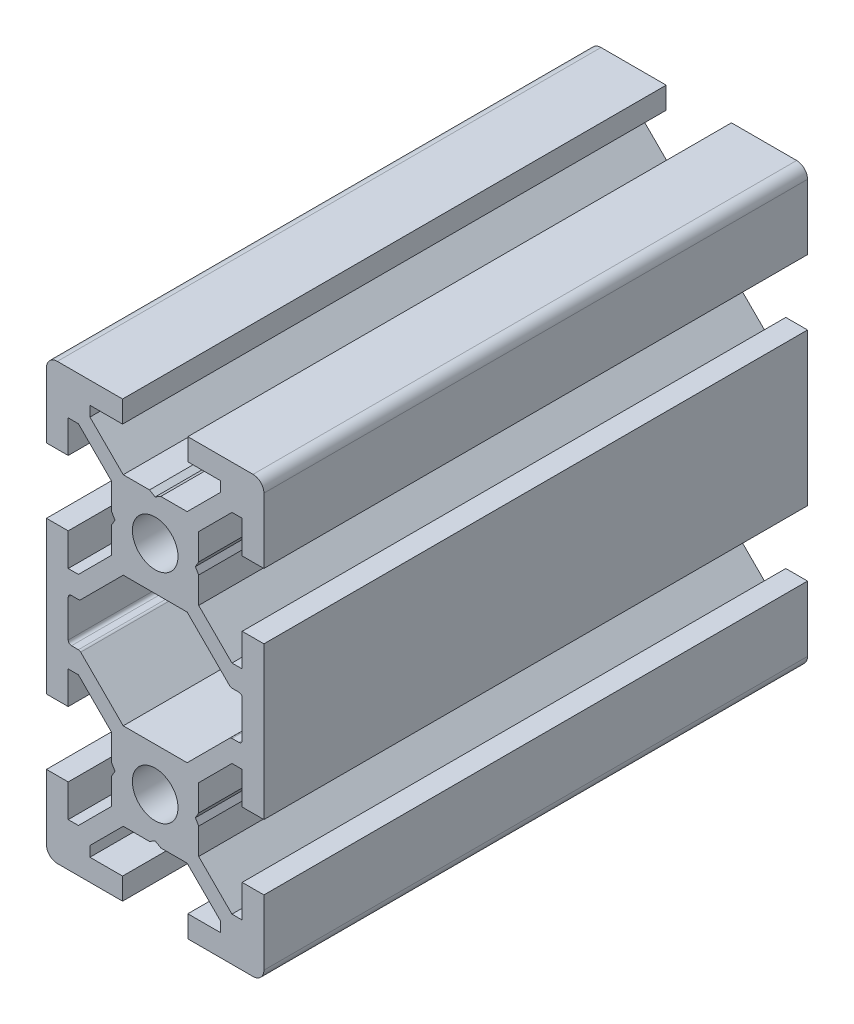
SolidWorks part; units mm, degrees
ref_plane "Front Plane" through (0, 0, 0) normal (0, 0, 1) x (1, 0, 0)
ref_plane "Top Plane" through (0, 0, 0) normal (0, 1, 0) x (1, 0, 0)
ref_plane "Right Plane" through (0, 0, 0) normal (1, 0, 0) x (0, 0, -1)
sketch "Sketch1" plane through (0, 0, 0) normal (0, 0, 1) x (1, 0, 0)
  line L0 (-8, -16) -> (-8, -13)
  line L1 (-8, -13) -> (-10, -13)
  line L2 (-10, -13) -> (-10, -19)
  line L3 (-9, -20) -> (-3, -20)
  line L4 (-3, -20) -> (-3, -18)
  line L5 (-3, -18) -> (-6, -18)
  line L6 (-6, -18) -> (-6, -17.0607)
  line L7 (-6, -17.0607) -> (-2.9393, -14)
  line L8 (-2.9393, -14) -> (-0.5196, -14)
  line L9 (-0.5196, -14) -> (0, -13.7)
  line L10 (0, -13.7) -> (0.5196, -14)
  line L11 (0.5196, -14) -> (2.9393, -14)
  line L12 (2.9393, -14) -> (6, -17.0607)
  line L13 (6, -17.0607) -> (6, -18)
  line L14 (6, -18) -> (3, -18)
  line L15 (3, -18) -> (3, -20)
  line L16 (3, -20) -> (9, -20)
  line L17 (10, -19) -> (10, -13)
  line L18 (10, -13) -> (8, -13)
  line L19 (8, -13) -> (8, -16)
  line L20 (8, -16) -> (7.0607, -16)
  line L21 (7.0607, -16) -> (4, -12.9393)
  line L22 (4, -12.9393) -> (4, -10.5196)
  line L23 (4, -10.5196) -> (3.7, -10)
  line L24 (3.7, -10) -> (4, -9.4804)
  line L25 (4, -9.4804) -> (4, -7.0607)
  line L26 (4, -7.0607) -> (7.0607, -4)
  line L27 (7.0607, -4) -> (8, -4)
  line L28 (8, -4) -> (8, -7)
  line L29 (8, -7) -> (10, -7)
  line L30 (10, -7) -> (10, 7)
  line L31 (10, 7) -> (8, 7)
  line L32 (8, 7) -> (8, 4)
  line L33 (8, 4) -> (7.0607, 4)
  line L34 (7.0607, 4) -> (4, 7.0607)
  line L35 (4, 7.0607) -> (4, 9.4804)
  line L36 (4, 9.4804) -> (3.7, 10)
  line L37 (3.7, 10) -> (4, 10.5196)
  line L38 (4, 10.5196) -> (4, 12.9393)
  line L39 (4, 12.9393) -> (7.0607, 16)
  line L40 (7.0607, 16) -> (8, 16)
  line L41 (8, 16) -> (8, 13)
  line L42 (8, 13) -> (10, 13)
  line L43 (10, 13) -> (10, 19)
  line L44 (9, 20) -> (3, 20)
  line L45 (3, 20) -> (3, 18)
  line L46 (3, 18) -> (6, 18)
  line L47 (6, 18) -> (6, 17.0607)
  line L48 (6, 17.0607) -> (2.9393, 14)
  line L49 (2.9393, 14) -> (0.5196, 14)
  line L50 (0.5196, 14) -> (0, 13.7)
  line L51 (0, 13.7) -> (-0.5196, 14)
  line L52 (-0.5196, 14) -> (-2.9393, 14)
  line L53 (-2.9393, 14) -> (-6, 17.0607)
  line L54 (-6, 17.0607) -> (-6, 18)
  line L55 (-6, 18) -> (-3, 18)
  line L56 (-3, 18) -> (-3, 20)
  line L57 (-3, 20) -> (-9, 20)
  line L58 (-10, 19) -> (-10, 13)
  line L59 (-10, 13) -> (-8, 13)
  line L60 (-8, 13) -> (-8, 16)
  line L61 (-8, 16) -> (-7.0607, 16)
  line L62 (-7.0607, 16) -> (-4, 12.9393)
  line L63 (-4, 12.9393) -> (-4, 10.5196)
  line L64 (-4, 10.5196) -> (-3.7, 10)
  line L65 (-3.7, 10) -> (-4, 9.4804)
  line L66 (-4, 9.4804) -> (-4, 7.0607)
  line L67 (-4, 7.0607) -> (-7.0607, 4)
  line L68 (-7.0607, 4) -> (-8, 4)
  line L69 (-8, 4) -> (-8, 7)
  line L70 (-8, 7) -> (-10, 7)
  line L71 (-10, 7) -> (-10, -7)
  line L72 (-10, -7) -> (-8, -7)
  line L73 (-8, -7) -> (-8, -4)
  line L74 (-8, -4) -> (-7.0607, -4)
  line L75 (-7.0607, -4) -> (-4, -7.0607)
  line L76 (-4, -7.0607) -> (-4, -9.4804)
  line L77 (-4, -9.4804) -> (-3.7, -10)
  line L78 (-3.7, -10) -> (-4, -10.5196)
  line L79 (-4, -10.5196) -> (-4, -12.9393)
  line L80 (-4, -12.9393) -> (-7.0607, -16)
  line L81 (-7.0607, -16) -> (-8, -16)
  line L82 (-7.0636, -2) -> (-7.7, -2)
  line L83 (-8, -1.7) -> (-8, 1.7)
  line L84 (-7.7, 2) -> (-7.0636, 2)
  line L85 (-6.8515, 2.0879) -> (-2.9393, 6)
  line L86 (-2.9393, 6) -> (2.9393, 6)
  line L87 (2.9393, 6) -> (6.8515, 2.0879)
  line L88 (7.0636, 2) -> (7.7, 2)
  line L89 (8, 1.7) -> (8, -1.7)
  line L90 (7.7, -2) -> (7.0636, -2)
  line L91 (6.8515, -2.0879) -> (2.9393, -6)
  line L92 (2.9393, -6) -> (-2.9393, -6)
  line L93 (-2.9393, -6) -> (-6.8515, -2.0879)
  circle A0 centre (0, -10) radius 2.1
  arc A1 (-10, -19) -> (-9, -20) centre (-9, -19) ccw
  arc A2 (9, -20) -> (10, -19) centre (9, -19) ccw
  arc A3 (10, 19) -> (9, 20) centre (9, 19) ccw
  arc A4 (-9, 20) -> (-10, 19) centre (-9, 19) ccw
  arc A5 (-7.7, -2) -> (-8, -1.7) centre (-7.7, -1.7) cw
  arc A6 (-8, 1.7) -> (-7.7, 2) centre (-7.7, 1.7) cw
  arc A7 (-7.0636, 2) -> (-6.8515, 2.0879) centre (-7.0636, 2.3) ccw
  arc A8 (6.8515, 2.0879) -> (7.0636, 2) centre (7.0636, 2.3) ccw
  arc A9 (7.7, 2) -> (8, 1.7) centre (7.7, 1.7) cw
  arc A10 (8, -1.7) -> (7.7, -2) centre (7.7, -1.7) cw
  arc A11 (7.0636, -2) -> (6.8515, -2.0879) centre (7.0636, -2.3) ccw
  arc A12 (-6.8515, -2.0879) -> (-7.0636, -2) centre (-7.0636, -2.3) ccw
  circle A13 centre (0, 10) radius 2.1
extrude "Boss-Extrude1" add sketch "Sketch1" against normal blind 50
